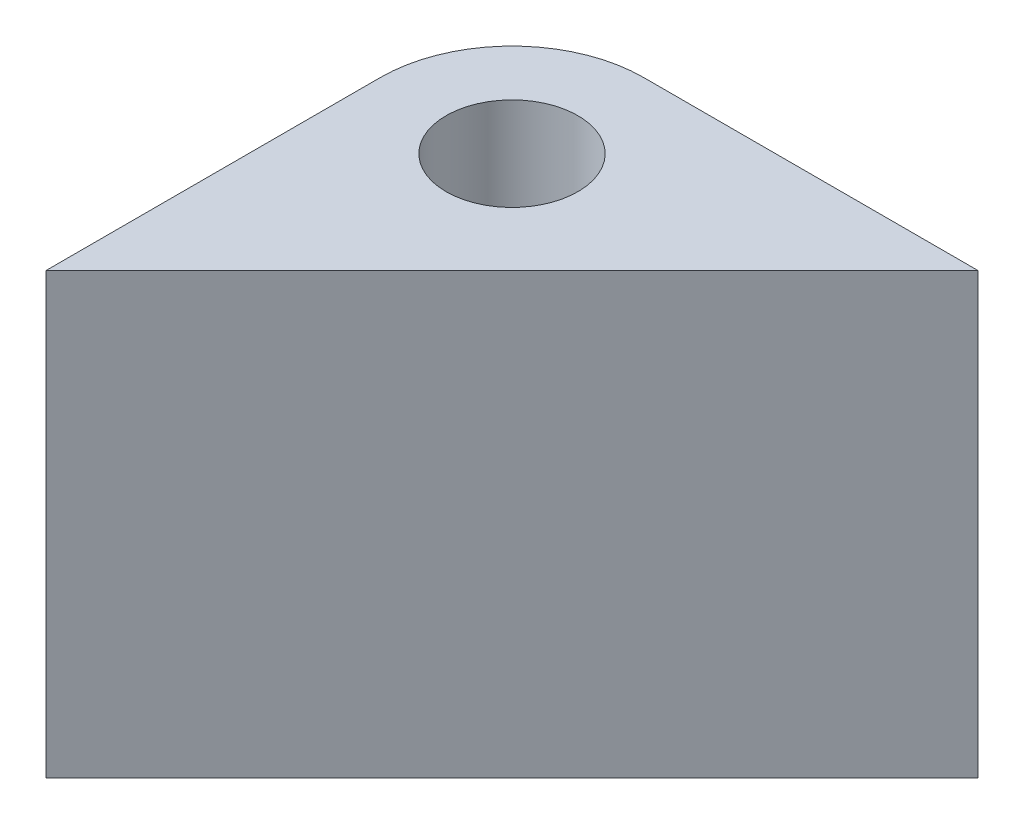
SolidWorks part; units mm, degrees
ref_plane "Front Plane" through (0, 0, 0) normal (0, 0, 1) x (1, 0, 0)
ref_plane "Top Plane" through (0, 0, 0) normal (0, 1, 0) x (1, 0, 0)
ref_plane "Right Plane" through (0, 0, 0) normal (1, 0, 0) x (0, 0, -1)
sketch "Sketch1" plane through (0, 0, 0) normal (0, 1, 0) x (1, 0, 0)
  line L0 (7.6066, 3) -> (0, 3)
  line L1 (-3, 0) -> (-3, -7.6066)
  line L2 (-3, -7.6066) -> (7.6066, 3)
  line L3 (0, 0) -> (2.3033, -2.3033) construction
  circle A0 centre (0, 0) radius 1.5
  arc A1 (0, 3) -> (-3, 0) centre (0, 0) ccw
  point P5 (-1.2, -5.8711)
  point P7 (-2.4583, -6.027)
  dimension "D1" = 3
  dimension "D3" = 3
  dimension "D2" = 15
extrude "Boss-Extrude1" add sketch "Sketch1" along normal blind 10
